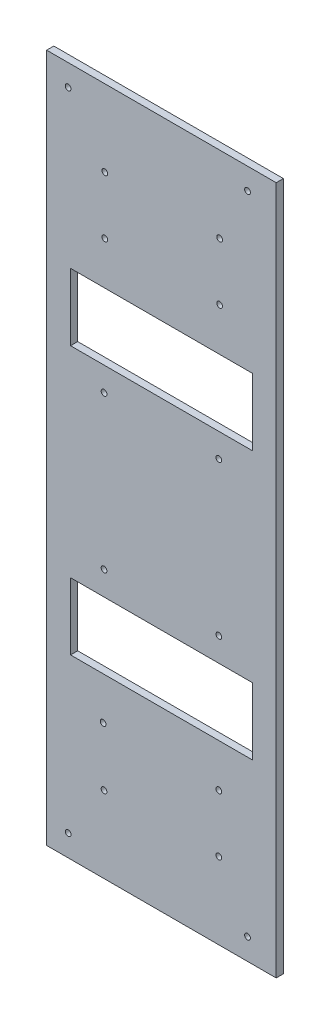
SolidWorks part; units mm, degrees
ref_plane "Front Plane" through (0, 0, 0) normal (0, 0, 1) x (1, 0, 0)
ref_plane "Top Plane" through (0, 0, 0) normal (0, 1, 0) x (1, 0, 0)
ref_plane "Right Plane" through (0, 0, 0) normal (1, 0, 0) x (0, 0, -1)
sketch "Sketch1" plane through (0, 0, 0) normal (0, 0, 1) x (1, 0, 0)
  line L0 (-180.4715, 360.5134) -> (-180.4715, -96.6866) construction
  line L1 (-194.7463, 360.5134) -> (-42.3463, 360.5134)
  line L2 (-194.7463, 360.5134) -> (-194.7463, -96.6866)
  line L3 (-194.7463, -96.6866) -> (-42.3463, -96.6866)
  line L4 (-42.3463, 360.5134) -> (-42.3463, -96.6866)
  line L5 (-194.7463, 360.5134) -> (-180.4715, 317.689) construction
  line L6 (-194.7463, -96.6866) -> (-180.4715, -53.8622) construction
  line L7 (-61.3963, 360.5134) -> (-61.3963, -96.6866) construction
  line L8 (-194.7463, 346.2386) -> (-42.3463, 346.2386) construction
  line L9 (-194.7463, -82.4118) -> (-42.3463, -82.4118) construction
  line L10 (-47.1046, 346.2386) -> (-42.3463, 360.5134) construction
  line L11 (-47.1046, -82.4118) -> (-42.3463, -96.6866) construction
  circle A0 centre (-61.3963, 346.2386) radius 1.905
  circle A1 centre (-180.4715, 346.2386) radius 1.905
  circle A2 centre (-180.4715, -82.4118) radius 1.905
  circle A3 centre (-61.3963, -82.4118) radius 1.905
  point P0 (-118.5463, 131.9134)
  dimension "D7" = 3.81
  dimension "D8" = 3.81
  dimension "D9" = 3.81
  dimension "D10" = 3.81
  dimension "D1" = 457.2
  dimension "D2" = 152.4
  dimension "D3" = 14.2748
  dimension "D4" = 14.2748
  dimension "D5" = 14.2748
  dimension "D6" = 19.05
extrude "Boss-Extrude1" add sketch "Sketch1" along normal blind 4.7625
sketch "Sketch3" plane through (0, 0, 4.7625) normal (0, 0, 1) x (1, 0, 0)
  circle A0 centre (-156.6336, 182.6545) radius 1.905
  circle A1 centre (-80.4336, 182.6545) radius 1.905
  circle A2 centre (-156.6336, 81.0545) radius 1.905
  circle A3 centre (-80.4336, 81.0545) radius 1.905
  dimension "D1" = 3.81
  dimension "D2" = 3.81
  dimension "D3" = 3.81
  dimension "D4" = 3.81
extrude "Cut-Extrude1" cut sketch "Sketch3" against normal up to next
sketch "Sketch6" plane through (0, 0, 4.7625) normal (0, 0, 1) x (1, 0, 0)
  line L0 (-182.0336, -71.2993) -> (-182.0336, 335.1007) construction
  line L1 (-58.2213, 20.7757) -> (-178.8586, 20.7757)
  line L2 (-58.2213, 20.7757) -> (-58.2213, 65.1795)
  line L3 (-58.2213, 65.1795) -> (-178.8586, 65.1795)
  line L4 (-178.8586, 20.7757) -> (-178.8586, 65.1795)
  line L5 (-58.2213, 198.5295) -> (-178.8586, 198.5295)
  line L6 (-58.2213, 198.5295) -> (-58.2213, 243.0257)
  line L7 (-58.2213, 243.0257) -> (-178.8586, 243.0257)
  line L8 (-178.8586, 198.5295) -> (-178.8586, 243.0257)
  line L9 (-55.0463, 17.6007) -> (-182.0463, 17.6007) construction
  line L10 (-55.0463, 339.8632) -> (-55.0463, -76.0618) construction
  line L11 (-182.0336, 68.3545) -> (-55.0336, 68.3545) construction
  line L12 (-55.0336, 195.3545) -> (-182.0336, 195.3545) construction
  line L13 (-55.0463, 332.2432) -> (-55.0463, -68.4418) construction
  line L14 (-54.5008, 246.2007) -> (-181.5008, 246.2007) construction
  dimension "D1" = 3.175
  dimension "D2" = 3.175
  dimension "D3" = 3.175
  dimension "D4" = 3.175
  dimension "D5" = 3.175
  dimension "D6" = 3.175
  dimension "D7" = 3.175
  dimension "D8" = 3.175
extrude "Cut-Extrude4" cut sketch "Sketch6" against normal up to next
sketch "Sketch7" plane through (0, 0, 4.7625) normal (0, 0, 1) x (1, 0, 0)
  circle A0 centre (-157.2367, -7.4322) radius 1.905
  circle A1 centre (-156.6463, -45.8993) radius 1.905
  circle A2 centre (-80.4463, -45.8993) radius 1.905
  circle A3 centre (-80.4463, -7.7993) radius 1.905
  circle A5 centre (-79.9008, 271.6007) radius 1.905
  circle A6 centre (-79.9008, 309.7007) radius 1.905
  circle A7 centre (-156.1008, 309.7007) radius 1.905
  circle A8 centre (-156.1008, 271.6007) radius 1.905
  dimension "D1" = 3.81
  dimension "D2" = 3.81
  dimension "D3" = 3.81
  dimension "D4" = 3.81
  dimension "D5" = 3.81
  dimension "D6" = 3.81
  dimension "D7" = 3.81
  dimension "D8" = 3.81
extrude "Cut-Extrude5" cut sketch "Sketch7" against normal through all
